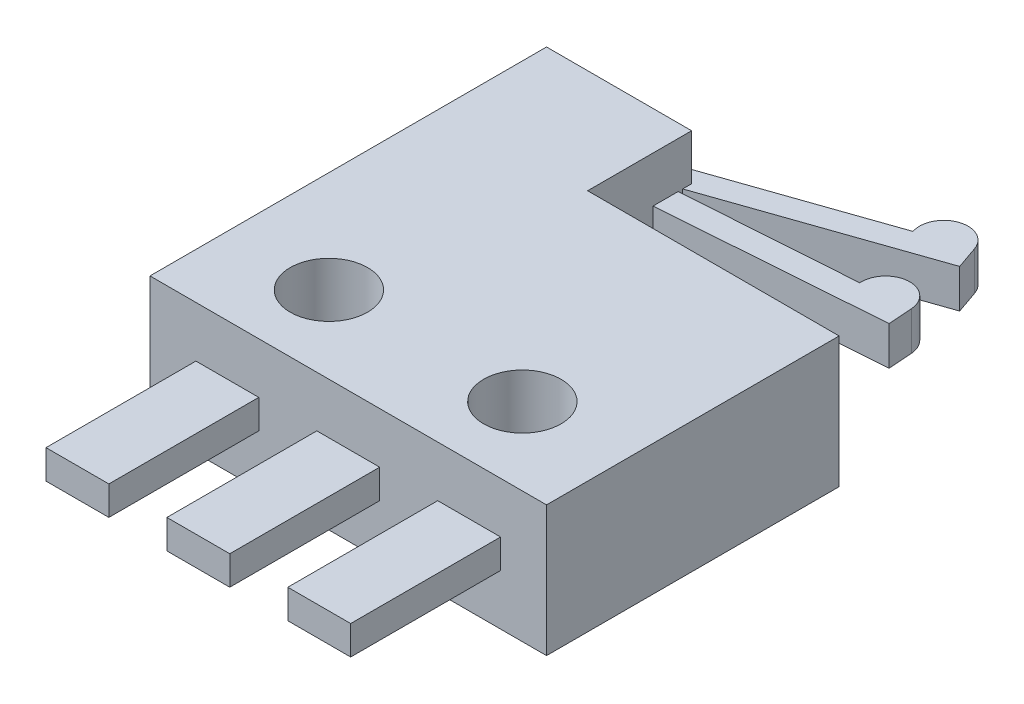
SolidWorks part; units mm, degrees
ref_plane "Front Plane" through (0, 0, 0) normal (0, 0, 1) x (1, 0, 0)
ref_plane "Top Plane" through (0, 0, 0) normal (0, 1, 0) x (1, 0, 0)
ref_plane "Right Plane" through (0, 0, 0) normal (1, 0, 0) x (0, 0, -1)
sketch "Sketch1" plane through (0, 0, 0) normal (0, 1, 0) x (1, 0, 0)
  line L1 (0, 0) -> (8.2, 0)
  line L2 (0, 0) -> (0, 6.05)
  line L3 (0, 6.05) -> (8.2, 6.05)
  line L4 (8.2, 0) -> (8.2, 6.05)
  line L5 (0, 6.05) -> (3, 6.05)
  line L6 (0, 6.05) -> (0, 8.2)
  line L7 (0, 8.2) -> (3, 8.2)
  line L8 (3, 6.05) -> (3, 8.2)
  dimension "D1" = 8.2
  dimension "D2" = 6.05
  dimension "D3" = 8.2
  dimension "D4" = 3
extrude "Body" add sketch "Sketch1" along normal blind 2.7 contours L3 L8 L7 L6 | L1 L4 L3 L2
ref_plane "Plane1" through (0, 1.35, 0) normal (0, 1, 0) x (1, 0, 0)
sketch "Sketch2" plane through (0, 1.35, 0) normal (0, 1, 0) x (1, 0, 0)
  line L0 (2.25, -3.1) -> (3.45, -3.1) construction
  line L1 (0.95, 0) -> (2.25, 0)
  line L2 (0.95, 0) -> (0.95, -3.1)
  line L3 (0.95, -3.1) -> (2.25, -3.1)
  line L4 (2.25, 0) -> (2.25, -3.1)
  line L5 (3.45, 0) -> (4.75, 0)
  line L6 (3.45, 0) -> (3.45, -3.1)
  line L7 (3.45, -3.1) -> (4.75, -3.1)
  line L8 (4.75, 0) -> (4.75, -3.1)
  line L9 (5.95, 0) -> (7.25, 0)
  line L10 (5.95, 0) -> (5.95, -3.1)
  line L11 (5.95, -3.1) -> (7.25, -3.1)
  line L12 (7.25, 0) -> (7.25, -3.1)
  line L13 (4.75, -3.1) -> (5.95, -3.1) construction
  line L14 (5.95, 0) -> (4.75, 0) construction
  line L15 (4.75, 0) -> (3.45, 0) construction
  line L16 (2.25, 0) -> (3.45, 0) construction
  line L17 (0, 0) -> (8.2, 0) construction
  point P12 (3.9183, -2.825)
  point P13 (1.6, -3.1)
  point P15 (6.6, -3.1)
  dimension "D1" = 3.1
  dimension "D2" = 1.3
  dimension "D3" = 1.6
  dimension "D4" = 1.6
extrude "Pins" add sketch "Sketch2" along normal blind 0.3 and the other way blind 0.3
sketch "Sketch3" plane through (0, 2.7, 0) normal (0, 1, 0) x (1, 0, 0)
  line L0 (2.1, 1.6) -> (6.1, 1.6) construction
  line L1 (0, 0) -> (8.2, 0) construction
  line L2 (0, 0) -> (0, 8.2) construction
  circle A0 centre (2.1, 1.6) radius 0.8
  circle A1 centre (6.1, 1.6) radius 0.8
  point P4 (2.3334, 1.7832)
  dimension "D2" = 1.6
  dimension "D1" = 4
  dimension "D3" = 1.6
  dimension "D4" = 2.1
extrude "M1.6Holes" cut sketch "Sketch3" against normal through all
sketch "Sketch4" plane through (0, 1.35, 0) normal (0, 1, 0) x (1, 0, 0)
  line L0 (0.75, 7.5) -> (6.6152, 9.8) construction
  line L1 (7.0875, 9.9639) -> (7.2514, 9.4916)
  line L2 (7.2514, 9.4916) -> (0.75, 7.2354)
  line L3 (0.75, 7.2354) -> (0.75, 7.7646)
  line L4 (0.75, 7.7646) -> (6.6152, 9.8)
  circle A0 centre (6.1, 1.6) radius 0.8 construction
  circle A1 centre (6.6152, 9.8) radius 0.5
  point P0 (0.75, 7.5)
  point P8 (6.6152, 10.3)
  point P9 (7.514, 9.3554)
  point P12 (7.4473, 8.9385)
  point P13 (1.998, 8.7595)
  point P14 (0.75, 7.5)
  point P15 (0.75, 7.937)
  dimension "D2" = 5.9
  dimension "D3" = 1
  dimension "D1" = 5.35
  dimension "D4" = 6.3
  dimension "D5" = 8.7
extrude "FreePosition" add sketch "Sketch4" along normal blind 0.4 and the other way blind 0.4 contours A1 L2 L1 | L0 A1 L4 | L0 L3 L2 A1 | L3 L0 A1 L4 | A1 L0 L4
sketch "Sketch5" plane through (0, 1.35, 0) normal (0, 1, 0) x (1, 0, 0)
  line L0 (7.0875, 9.9639) -> (7.2514, 9.4916) construction
  line L1 (7.2514, 9.4916) -> (0.75, 7.2354) construction
  line L2 (0.75, 7.2354) -> (0.75, 7.7646) construction
  line L3 (0.75, 7.7646) -> (6.6152, 9.8) construction
  line L4 (7.0875, 9.9639) -> (7.2514, 9.4916) construction
  line L5 (7.2514, 9.4916) -> (0.75, 7.2354) construction
  line L6 (0.75, 7.2354) -> (0.75, 7.7646)
  line L7 (0.75, 7.7646) -> (6.6152, 9.8) construction
  line L8 (0.75, 7.5) -> (7.011, 8.2) construction
  line L9 (0.75, 7.7646) -> (7.011, 8.2)
  line L10 (7.011, 8.2) -> (7.5098, 8.2347)
  line L11 (7.5098, 8.2347) -> (7.5443, 7.7381)
  line L12 (7.5443, 7.7381) -> (0.75, 7.2354)
  circle A0 centre (7.011, 8.2) radius 0.5
  circle A1 centre (6.6152, 9.8) radius 0.5
  circle A2 centre (6.6152, 9.8) radius 0.5 construction
  circle A3 centre (6.1, 1.6) radius 0.8 construction
  point P18 (7.011, 8.7)
  dimension "D2" = 1
  dimension "D3" = 6.3
  dimension "D4" = 7.1
  dimension "D1" = 0
extrude "OperatingPoint" add sketch "Sketch5" along normal blind 0.4 and the other way blind 0.4 contours A0 L9 L6 L12 | A0 L12 L11 | A0 L10 L9 | L10 A0 L9
